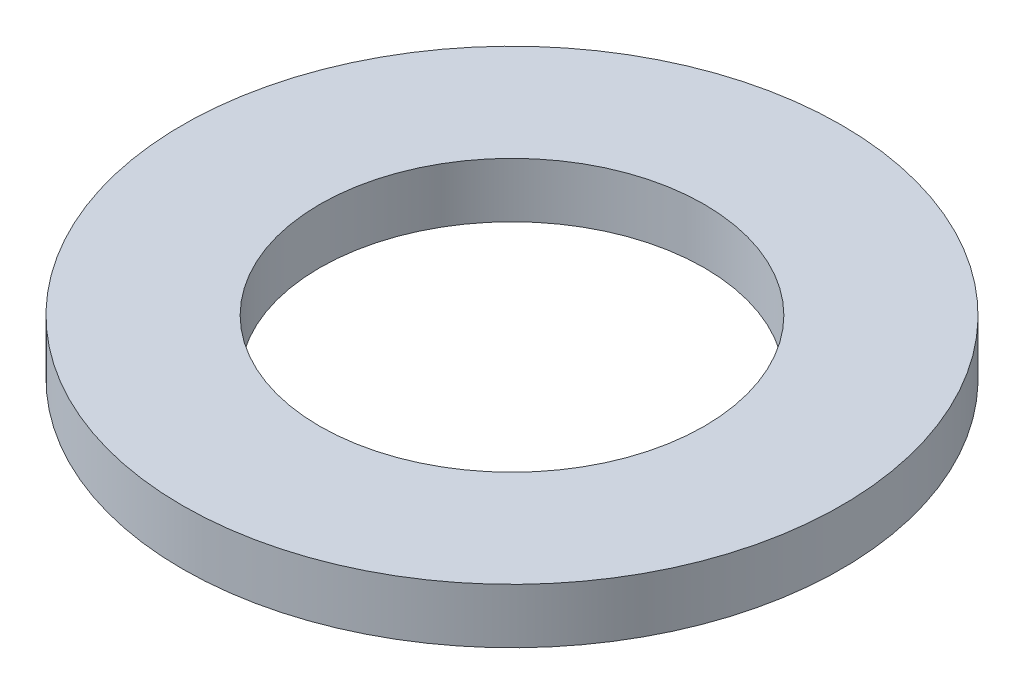
SolidWorks part; units mm, degrees
ref_plane "Front Plane" through (0, 0, 0) normal (0, 0, 1) x (1, 0, 0)
ref_plane "Top Plane" through (0, 0, 0) normal (0, 1, 0) x (1, 0, 0)
ref_plane "Right Plane" through (0, 0, 0) normal (1, 0, 0) x (0, 0, -1)
sketch "Sketch1" plane through (0, 0, 0) normal (0, 1, 0) x (1, 0, 0)
  circle A0 centre (0, 0) radius 6
  circle A1 centre (0, 0) radius 3.5
extrude "Boss-Extrude1" add sketch "Sketch1" along normal blind 1
